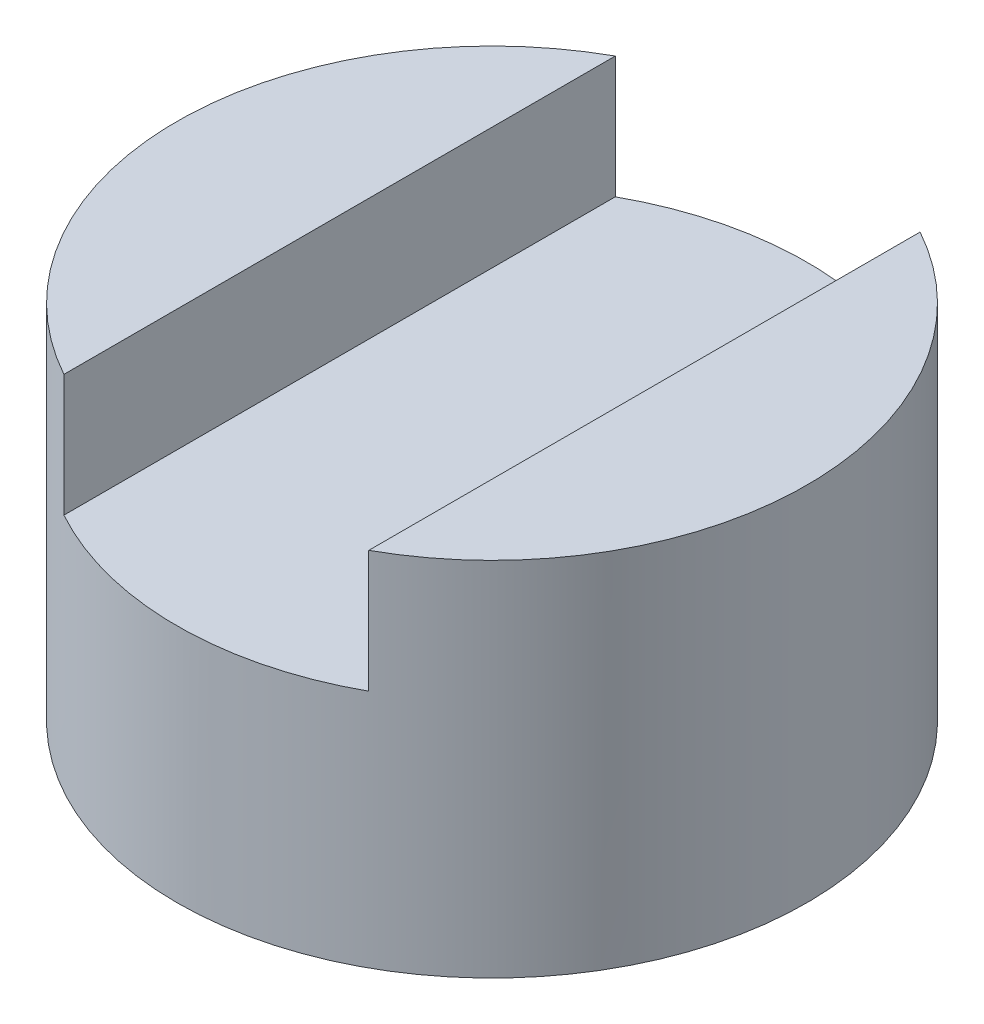
SolidWorks part; units mm, degrees
material "普通碳钢"
ref_plane "前视基准面" through (0, 0, 0) normal (0, 0, 1) x (1, 0, 0)
ref_plane "上视基准面" through (0, 0, 0) normal (0, 1, 0) x (1, 0, 0)
ref_plane "右视基准面" through (0, 0, 0) normal (1, 0, 0) x (0, 0, -1)
sketch "草图1" plane through (0, 0, 0) normal (0, 1, 0) x (1, 0, 0)
  circle A0 centre (0, 0) radius 15.5
  dimension "D1" = 31
extrude "凸台-拉伸1" add sketch "草图1" along normal blind 17.8
sketch "草图2" plane through (0, 17.8, 0) normal (0, 1, 0) x (1, 0, 0)
  line L0 (7.5, 13.5647) -> (-7.5, -13.5647) construction
  line L1 (-7.5, 13.5647) -> (-7.5, -13.5647)
  line L2 (7.5, 13.5647) -> (7.5, -13.5647)
  circle A0 centre (0, 0) radius 15.5 construction
  arc A1 (-7.5, 13.5647) -> (7.5, 13.5647) centre (0, 0) cw
  arc A2 (-7.5, -13.5647) -> (7.5, -13.5647) centre (0, 0) ccw
  point P4 (0, 0)
  point P10 (-7.5, 0)
  point P13 (7.5, 0)
  dimension "D2" = 15.5
  dimension "D1" = 15
  dimension "D3" = 27.1293
extrude "切除-拉伸1" cut sketch "草图2" against normal blind 6
